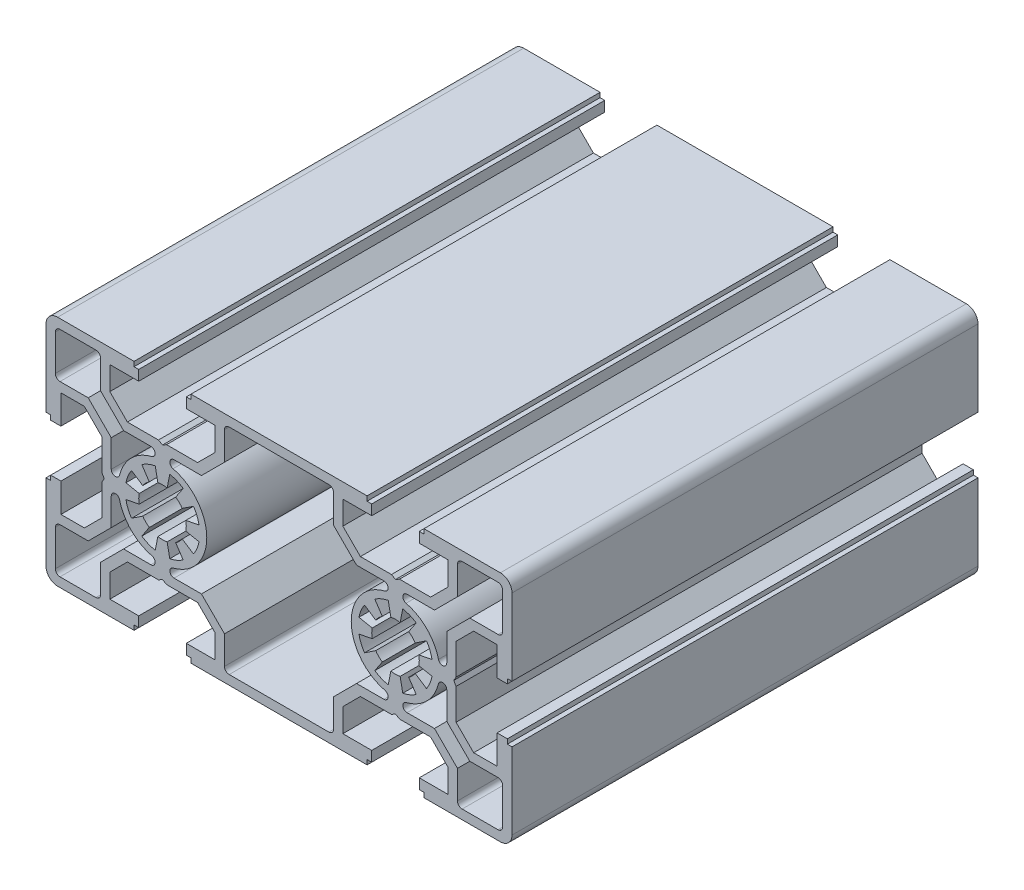
SolidWorks part; units mm, degrees
ref_plane "前视基准面" through (0, 0, 0) normal (0, 0, 1) x (1, 0, 0)
ref_plane "上视基准面" through (0, 0, 0) normal (0, 1, 0) x (1, 0, 0)
ref_plane "右视基准面" through (0, 0, 0) normal (1, 0, 0) x (0, 0, -1)
sketch "草图1" plane through (0, 0, 0) normal (0, 0, 1) x (1, 0, 0)
  line B0 (75, 6.1) -> (75, 22.5)
  line B1 (72.5, 25) -> (56.1, 25)
  line B2 (56.1, 25) -> (56.1, 24)
  line B3 (56.1, 24) -> (55.1, 24)
  line B4 (55.1, 24) -> (55.1, 21.8)
  line B5 (55.1, 21.8) -> (61.3, 21.8)
  line B6 (61.3, 21.8) -> (61.3, 16.7698)
  line B7 (61.3, 16.7698) -> (57.5302, 13)
  line B8 (57.5302, 13) -> (50.866, 13)
  line B9 (50.866, 13) -> (50, 12.5)
  line B10 (50, 12.5) -> (49.134, 13)
  line B11 (49.134, 13) -> (42.4698, 13)
  line B12 (42.4698, 13) -> (38.7, 16.7698)
  line B13 (38.7, 16.7698) -> (38.7, 21.8)
  line B14 (38.7, 21.8) -> (44.9, 21.8)
  line B15 (44.9, 21.8) -> (44.9, 24)
  line B16 (44.9, 24) -> (43.9, 24)
  line B17 (43.9, 24) -> (43.9, 25)
  line B18 (43.9, 25) -> (6.1, 25)
  line B19 (6.1, 25) -> (6.1, 24)
  line B20 (6.1, 24) -> (5.1, 24)
  line B21 (5.1, 24) -> (5.1, 21.8)
  line B22 (5.1, 21.8) -> (11.3, 21.8)
  line B23 (11.3, 21.8) -> (11.3, 16.7698)
  line B24 (11.3, 16.7698) -> (7.5302, 13)
  line B25 (7.5302, 13) -> (0.866, 13)
  line B26 (0.866, 13) -> (0, 12.5)
  line B27 (0, 12.5) -> (-0.866, 13)
  line B28 (-0.866, 13) -> (-7.5302, 13)
  line B29 (-7.5302, 13) -> (-11.3, 16.7698)
  line B30 (-11.3, 16.7698) -> (-11.3, 21.8)
  line B31 (-11.3, 21.8) -> (-5.1, 21.8)
  line B32 (-5.1, 21.8) -> (-5.1, 24)
  line B33 (-5.1, 24) -> (-6.1, 24)
  line B34 (-6.1, 24) -> (-6.1, 25)
  line B35 (-6.1, 25) -> (-22.5, 25)
  line B36 (-25, 22.5) -> (-25, 6.1)
  line B37 (-25, 6.1) -> (-24, 6.1)
  line B38 (-24, 6.1) -> (-24, 5.1)
  line B39 (-24, 5.1) -> (-21.8, 5.1)
  line B40 (-21.8, 5.1) -> (-21.8, 11.3)
  line B41 (-21.8, 11.3) -> (-16.7698, 11.3)
  line B42 (-16.7698, 11.3) -> (-13, 7.5302)
  line B43 (-13, 7.5302) -> (-13, 0.866)
  line B44 (-13, 0.866) -> (-12.5, 0)
  line B45 (-12.5, 0) -> (-13, -0.866)
  line B46 (-13, -0.866) -> (-13, -7.5302)
  line B47 (-13, -7.5302) -> (-16.7698, -11.3)
  line B48 (-16.7698, -11.3) -> (-21.8, -11.3)
  line B49 (-21.8, -11.3) -> (-21.8, -5.1)
  line B50 (-21.8, -5.1) -> (-24, -5.1)
  line B51 (-24, -5.1) -> (-24, -6.1)
  line B52 (-24, -6.1) -> (-25, -6.1)
  line B53 (-25, -6.1) -> (-25, -22.5)
  line B54 (-22.5, -25) -> (-6.1, -25)
  line B55 (-6.1, -25) -> (-6.1, -24)
  line B56 (-6.1, -24) -> (-5.1, -24)
  line B57 (-5.1, -24) -> (-5.1, -21.8)
  line B58 (-5.1, -21.8) -> (-11.3, -21.8)
  line B59 (-11.3, -21.8) -> (-11.3, -16.7698)
  line B60 (-11.3, -16.7698) -> (-7.5302, -13)
  line B61 (-7.5302, -13) -> (-0.866, -13)
  line B62 (-0.866, -13) -> (0, -12.5)
  line B63 (0, -12.5) -> (0.866, -13)
  line B64 (0.866, -13) -> (7.5302, -13)
  line B65 (7.5302, -13) -> (11.3, -16.7698)
  line B66 (11.3, -16.7698) -> (11.3, -21.8)
  line B67 (11.3, -21.8) -> (5.1, -21.8)
  line B68 (5.1, -21.8) -> (5.1, -24)
  line B69 (5.1, -24) -> (6.1, -24)
  line B70 (6.1, -24) -> (6.1, -25)
  line B71 (6.1, -25) -> (43.9, -25)
  line B72 (43.9, -25) -> (43.9, -24)
  line B73 (43.9, -24) -> (44.9, -24)
  line B74 (44.9, -24) -> (44.9, -21.8)
  line B75 (44.9, -21.8) -> (38.7, -21.8)
  line B76 (38.7, -21.8) -> (38.7, -16.7698)
  line B77 (38.7, -16.7698) -> (42.4698, -13)
  line B78 (42.4698, -13) -> (49.134, -13)
  line B79 (49.134, -13) -> (50, -12.5)
  line B80 (50, -12.5) -> (50.866, -13)
  line B81 (50.866, -13) -> (57.5302, -13)
  line B82 (57.5302, -13) -> (61.3, -16.7698)
  line B83 (61.3, -16.7698) -> (61.3, -21.8)
  line B84 (61.3, -21.8) -> (55.1, -21.8)
  line B85 (55.1, -21.8) -> (55.1, -24)
  line B86 (55.1, -24) -> (56.1, -24)
  line B87 (56.1, -24) -> (56.1, -25)
  line B88 (56.1, -25) -> (72.5, -25)
  line B89 (75, -22.5) -> (75, -6.1)
  line B90 (75, -6.1) -> (74, -6.1)
  line B91 (74, -6.1) -> (74, -5.1)
  line B92 (74, -5.1) -> (71.8, -5.1)
  line B93 (71.8, -5.1) -> (71.8, -11.3)
  line B94 (71.8, -11.3) -> (66.7698, -11.3)
  line B95 (66.7698, -11.3) -> (63, -7.5302)
  line B96 (63, -7.5302) -> (63, -0.866)
  line B97 (63, -0.866) -> (62.5, 0)
  line B98 (62.5, 0) -> (63, 0.866)
  line B99 (63, 0.866) -> (63, 7.5302)
  line B100 (63, 7.5302) -> (66.7698, 11.3)
  line B101 (66.7698, 11.3) -> (71.8, 11.3)
  line B102 (71.8, 11.3) -> (71.8, 5.1)
  line B103 (71.8, 5.1) -> (74, 5.1)
  line B104 (74, 5.1) -> (74, 6.1)
  line B105 (74, 6.1) -> (75, 6.1)
  line B106 (61, -2.4799) -> (61, -8.3586)
  line B107 (61, -8.3586) -> (65.9414, -13.3)
  line B108 (65.9414, -13.3) -> (72, -13.3)
  line B109 (73, -14.3) -> (73, -22)
  line B110 (72, -23) -> (64.3, -23)
  line B111 (63.3, -22) -> (63.3, -15.9414)
  line B112 (63.3, -15.9414) -> (58.3586, -11)
  line B113 (58.3586, -11) -> (52.4799, -11)
  line B114 (52.8334, 4.2405) -> (54.4446, 6.6518)
  line B115 (51.5607, 7.8463) -> (50.995, 5.002)
  line B116 (49.005, 5.002) -> (48.4393, 7.8463)
  line B117 (45.5554, 6.6518) -> (47.1666, 4.2405)
  line B118 (45.7595, 2.8334) -> (43.3482, 4.4446)
  line B119 (42.1537, 1.5607) -> (44.998, 0.995)
  line B120 (44.998, -0.995) -> (42.1537, -1.5607)
  line B121 (43.3482, -4.4446) -> (45.7595, -2.8334)
  line B122 (47.1666, -4.2405) -> (45.5554, -6.6518)
  line B123 (48.4393, -7.8463) -> (49.005, -5.002)
  line B124 (50.995, -5.002) -> (51.5607, -7.8463)
  line B125 (54.4446, -6.6518) -> (52.8334, -4.2405)
  line B126 (54.2405, -2.8334) -> (56.6518, -4.4446)
  line B127 (57.8463, -1.5607) -> (55.002, -0.995)
  line B128 (55.002, 0.995) -> (57.8463, 1.5607)
  line B129 (56.6518, 4.4446) -> (54.2405, 2.8334)
  line B130 (65.9414, 13.3) -> (61, 8.3586)
  line B131 (61, 8.3586) -> (61, 2.4799)
  line B132 (52.4799, 11) -> (58.3586, 11)
  line B133 (58.3586, 11) -> (63.3, 15.9414)
  line B134 (63.3, 15.9414) -> (63.3, 22)
  line B135 (64.3, 23) -> (72, 23)
  line B136 (73, 22) -> (73, 14.3)
  line B137 (72, 13.3) -> (65.9414, 13.3)
  line B138 (47.5201, -11) -> (41.6414, -11)
  line B139 (41.6414, -11) -> (36.7, -15.9414)
  line B140 (36.7, -15.9414) -> (36.7, -22)
  line B141 (35.7, -23) -> (14.3, -23)
  line B142 (13.3, -22) -> (13.3, -15.9414)
  line B143 (13.3, -15.9414) -> (8.3586, -11)
  line B144 (8.3586, -11) -> (2.4799, -11)
  line B145 (2.4799, 11) -> (8.3586, 11)
  line B146 (8.3586, 11) -> (13.3, 15.9414)
  line B147 (13.3, 15.9414) -> (13.3, 22)
  line B148 (14.3, 23) -> (35.7, 23)
  line B149 (36.7, 22) -> (36.7, 15.9414)
  line B150 (36.7, 15.9414) -> (41.6414, 11)
  line B151 (41.6414, 11) -> (47.5201, 11)
  line B152 (-11, -2.4799) -> (-11, -8.3586)
  line B153 (-11, -8.3586) -> (-15.9414, -13.3)
  line B154 (-15.9414, -13.3) -> (-22, -13.3)
  line B155 (-23, -14.3) -> (-23, -22)
  line B156 (-22, -23) -> (-14.3, -23)
  line B157 (-13.3, -22) -> (-13.3, -15.9414)
  line B158 (-13.3, -15.9414) -> (-8.3586, -11)
  line B159 (-8.3586, -11) -> (-2.4799, -11)
  line B160 (-4.2405, 2.8334) -> (-6.6518, 4.4446)
  line B161 (-7.8463, 1.5607) -> (-5.002, 0.995)
  line B162 (-5.002, -0.995) -> (-7.8463, -1.5607)
  line B163 (-6.6518, -4.4446) -> (-4.2405, -2.8334)
  line B164 (-2.8334, -4.2405) -> (-4.4446, -6.6518)
  line B165 (-1.5607, -7.8463) -> (-0.995, -5.002)
  line B166 (0.995, -5.002) -> (1.5607, -7.8463)
  line B167 (4.4446, -6.6518) -> (2.8334, -4.2405)
  line B168 (4.2405, -2.8334) -> (6.6518, -4.4446)
  line B169 (7.8463, -1.5607) -> (5.002, -0.995)
  line B170 (5.002, 0.995) -> (7.8463, 1.5607)
  line B171 (6.6518, 4.4446) -> (4.2405, 2.8334)
  line B172 (2.8334, 4.2405) -> (4.4446, 6.6518)
  line B173 (1.5607, 7.8463) -> (0.995, 5.002)
  line B174 (-0.995, 5.002) -> (-1.5607, 7.8463)
  line B175 (-4.4446, 6.6518) -> (-2.8334, 4.2405)
  line B176 (-15.9414, 13.3) -> (-11, 8.3586)
  line B177 (-11, 8.3586) -> (-11, 2.4799)
  line B178 (-2.4799, 11) -> (-8.3586, 11)
  line B179 (-8.3586, 11) -> (-13.3, 15.9414)
  line B180 (-13.3, 15.9414) -> (-13.3, 22)
  line B181 (-14.3, 23) -> (-22, 23)
  line B182 (-23, 22) -> (-23, 14.3)
  line B183 (-22, 13.3) -> (-15.9414, 13.3)
  arc B184 (75, 22.5) -> (72.5, 25) centre (72.5, 22.5) ccw
  arc B185 (-22.5, 25) -> (-25, 22.5) centre (-22.5, 22.5) ccw
  arc B186 (-25, -22.5) -> (-22.5, -25) centre (-22.5, -22.5) ccw
  arc B187 (72.5, -25) -> (75, -22.5) centre (72.5, -22.5) ccw
  arc B188 (73, -14.3) -> (72, -13.3) centre (72, -14.3) ccw
  arc B189 (72, -23) -> (73, -22) centre (72, -22) ccw
  arc B190 (63.3, -22) -> (64.3, -23) centre (64.3, -22) ccw
  arc B191 (52.2653, -9.226) -> (52.4799, -11) centre (52.4799, -10.1) ccw
  arc B192 (52.2653, -9.226) -> (59.226, -2.2653) centre (50, 0) ccw
  arc B193 (61, -2.4799) -> (59.226, -2.2653) centre (60.1, -2.4799) ccw
  arc B194 (54.2405, 2.8334) -> (52.8334, 4.2405) centre (50, 0) ccw
  arc B195 (54.4446, 6.6518) -> (51.5607, 7.8463) centre (50, 0) ccw
  arc B196 (50.995, 5.002) -> (49.005, 5.002) centre (50, 0) ccw
  arc B197 (48.4393, 7.8463) -> (45.5554, 6.6518) centre (50, 0) ccw
  arc B198 (47.1666, 4.2405) -> (45.7595, 2.8334) centre (50, 0) ccw
  arc B199 (43.3482, 4.4446) -> (42.1537, 1.5607) centre (50, 0) ccw
  arc B200 (44.998, 0.995) -> (44.998, -0.995) centre (50, 0) ccw
  arc B201 (42.1537, -1.5607) -> (43.3482, -4.4446) centre (50, 0) ccw
  arc B202 (45.7595, -2.8334) -> (47.1666, -4.2405) centre (50, 0) ccw
  arc B203 (45.5554, -6.6518) -> (48.4393, -7.8463) centre (50, 0) ccw
  arc B204 (49.005, -5.002) -> (50.995, -5.002) centre (50, 0) ccw
  arc B205 (51.5607, -7.8463) -> (54.4446, -6.6518) centre (50, 0) ccw
  arc B206 (52.8334, -4.2405) -> (54.2405, -2.8334) centre (50, 0) ccw
  arc B207 (56.6518, -4.4446) -> (57.8463, -1.5607) centre (50, 0) ccw
  arc B208 (55.002, -0.995) -> (55.002, 0.995) centre (50, 0) ccw
  arc B209 (57.8463, 1.5607) -> (56.6518, 4.4446) centre (50, 0) ccw
  arc B210 (59.226, 2.2653) -> (61, 2.4799) centre (60.1, 2.4799) ccw
  arc B211 (59.226, 2.2653) -> (52.2653, 9.226) centre (50, 0) ccw
  arc B212 (52.4799, 11) -> (52.2653, 9.226) centre (52.4799, 10.1) ccw
  arc B213 (64.3, 23) -> (63.3, 22) centre (64.3, 22) ccw
  arc B214 (73, 22) -> (72, 23) centre (72, 22) ccw
  arc B215 (72, 13.3) -> (73, 14.3) centre (72, 14.3) ccw
  arc B216 (47.7347, 9.226) -> (40.774, 2.2653) centre (50, 0) ccw
  arc B217 (40.774, 2.2653) -> (47.7347, -9.226) centre (50, 0) ccw
  arc B218 (47.5201, -11) -> (47.7347, -9.226) centre (47.5201, -10.1) ccw
  arc B219 (35.7, -23) -> (36.7, -22) centre (35.7, -22) ccw
  arc B220 (13.3, -22) -> (14.3, -23) centre (14.3, -22) ccw
  arc B221 (2.2653, -9.226) -> (2.4799, -11) centre (2.4799, -10.1) ccw
  arc B222 (2.2653, -9.226) -> (9.226, 2.2653) centre (0, 0) ccw
  arc B223 (9.226, 2.2653) -> (2.2653, 9.226) centre (0, 0) ccw
  arc B224 (2.4799, 11) -> (2.2653, 9.226) centre (2.4799, 10.1) ccw
  arc B225 (14.3, 23) -> (13.3, 22) centre (14.3, 22) ccw
  arc B226 (36.7, 22) -> (35.7, 23) centre (35.7, 22) ccw
  arc B227 (47.7347, 9.226) -> (47.5201, 11) centre (47.5201, 10.1) ccw
  arc B228 (-22, -13.3) -> (-23, -14.3) centre (-22, -14.3) ccw
  arc B229 (-23, -22) -> (-22, -23) centre (-22, -22) ccw
  arc B230 (-14.3, -23) -> (-13.3, -22) centre (-14.3, -22) ccw
  arc B231 (-2.4799, -11) -> (-2.2653, -9.226) centre (-2.4799, -10.1) ccw
  arc B232 (-9.226, -2.2653) -> (-2.2653, -9.226) centre (0, 0) ccw
  arc B233 (-9.226, -2.2653) -> (-11, -2.4799) centre (-10.1, -2.4799) ccw
  arc B234 (-2.8334, 4.2405) -> (-4.2405, 2.8334) centre (0, 0) ccw
  arc B235 (-6.6518, 4.4446) -> (-7.8463, 1.5607) centre (0, 0) ccw
  arc B236 (-5.002, 0.995) -> (-5.002, -0.995) centre (0, 0) ccw
  arc B237 (-7.8463, -1.5607) -> (-6.6518, -4.4446) centre (0, 0) ccw
  arc B238 (-4.2405, -2.8334) -> (-2.8334, -4.2405) centre (0, 0) ccw
  arc B239 (-4.4446, -6.6518) -> (-1.5607, -7.8463) centre (0, 0) ccw
  arc B240 (-0.995, -5.002) -> (0.995, -5.002) centre (0, 0) ccw
  arc B241 (1.5607, -7.8463) -> (4.4446, -6.6518) centre (0, 0) ccw
  arc B242 (2.8334, -4.2405) -> (4.2405, -2.8334) centre (0, 0) ccw
  arc B243 (6.6518, -4.4446) -> (7.8463, -1.5607) centre (0, 0) ccw
  arc B244 (5.002, -0.995) -> (5.002, 0.995) centre (0, 0) ccw
  arc B245 (7.8463, 1.5607) -> (6.6518, 4.4446) centre (0, 0) ccw
  arc B246 (4.2405, 2.8334) -> (2.8334, 4.2405) centre (0, 0) ccw
  arc B247 (4.4446, 6.6518) -> (1.5607, 7.8463) centre (0, 0) ccw
  arc B248 (0.995, 5.002) -> (-0.995, 5.002) centre (0, 0) ccw
  arc B249 (-1.5607, 7.8463) -> (-4.4446, 6.6518) centre (0, 0) ccw
  arc B250 (-11, 2.4799) -> (-9.226, 2.2653) centre (-10.1, 2.4799) ccw
  arc B251 (-2.2653, 9.226) -> (-9.226, 2.2653) centre (0, 0) ccw
  arc B252 (-2.2653, 9.226) -> (-2.4799, 11) centre (-2.4799, 10.1) ccw
  arc B253 (-13.3, 22) -> (-14.3, 23) centre (-14.3, 22) ccw
  arc B254 (-22, 23) -> (-23, 22) centre (-22, 22) ccw
  arc B255 (-23, 14.3) -> (-22, 13.3) centre (-22, 14.3) ccw
sketch_block_instance "A$C08DC5F56-1"
sketch_block "A$C08DC5F56"
extrude "凸台-拉伸1" add sketch "草图1" along normal blind 100
